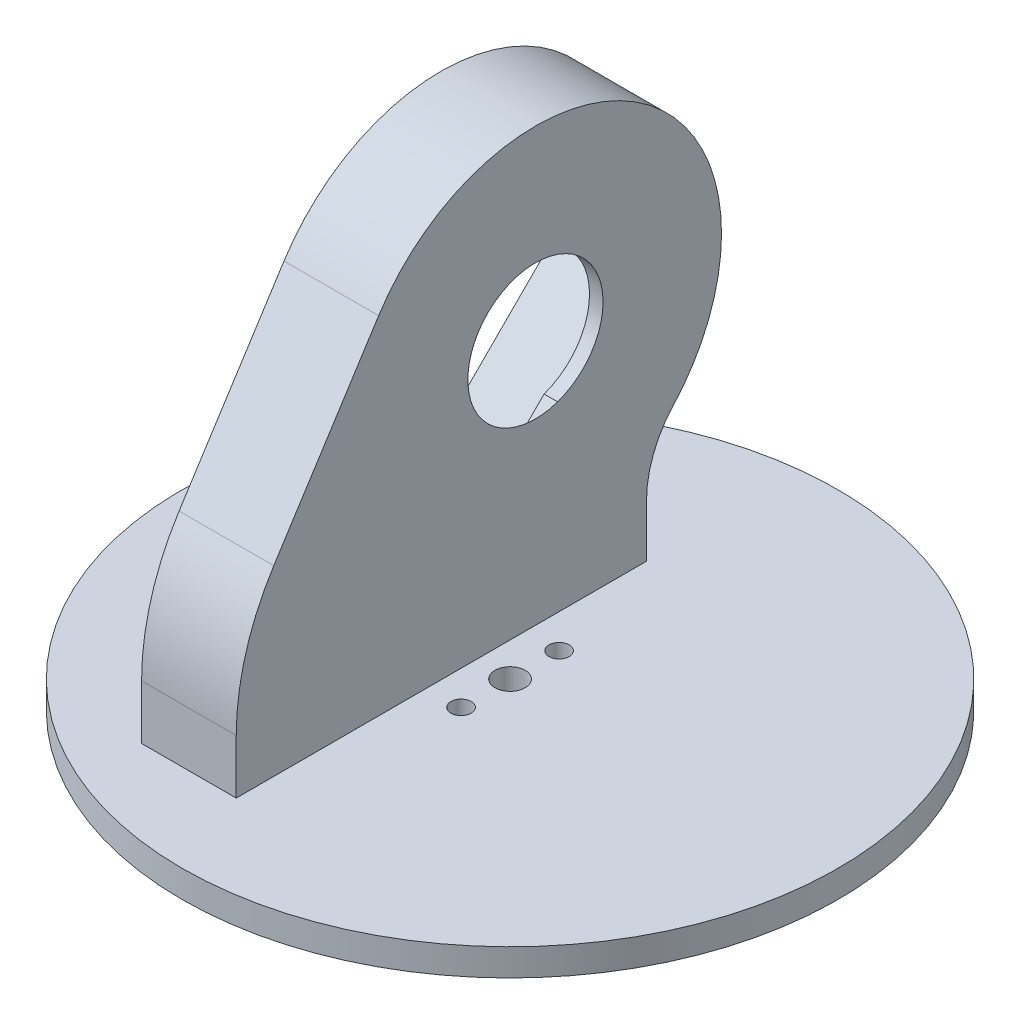
SolidWorks part; units mm, degrees
material "Acrylic (Medium-high impact)"
ref_plane "Front Plane" through (0, 0, 0) normal (0, 0, 1) x (1, 0, 0)
ref_plane "Top Plane" through (0, 0, 0) normal (0, 1, 0) x (1, 0, 0)
ref_plane "Right Plane" through (0, 0, 0) normal (1, 0, 0) x (0, 0, -1)
sketch "Sketch1" plane through (0, 0, 0) normal (0, 1, 0) x (1, 0, 0)
  line L0 (0, 51.8022) -> (0, -53.3582) construction
  circle A0 centre (0, 0) radius 48.5
  circle A1 centre (0, 7.25) radius 1.5
  circle A2 centre (0, -7.25) radius 1.5
  circle A3 centre (0, 0) radius 2.2356
  point P12 (0, 0)
  dimension "D1" = 97
  dimension "D2" = 3
  dimension "D3" = 3
  dimension "D4" = 14.5
  dimension "D5" = 7.25
extrude "Boss-Extrude2" add sketch "Sketch1" along normal blind 4
ref_plane "Plane2" through (-5, 0, 0) normal (1, 0, 0) x (0, 0, -1)
sketch "Sketch6" plane through (-5, 0, 0) normal (1, 0, 0) x (0, 0, -1)
  line L0 (25.18, 4) -> (-35.5, 4)
  line L1 (25.18, 4) -> (25.18, 11.7973)
  line L2 (-35.5, 4) -> (-35.5, 12.0173)
  line L3 (-29.9527, 30.9934) -> (-14.4381, 55.2614)
  line L4 (48.5, 4) -> (-48.5, 4) construction
  arc A0 (25.18, 11.7973) -> (29.0927, 21.9003) centre (40.18, 11.7973) cw
  arc A1 (29.0927, 21.9003) -> (-14.4381, 55.2614) centre (8.75, 40.4373) ccw
  arc A2 (-35.5, 12.0173) -> (-29.9527, 30.9934) centre (-0.27, 12.0173) cw
  circle A3 centre (8.75, 40.4373) radius 10
  point P3 (-5.16, 4)
  dimension "D2" = 20
  dimension "D1" = 13
extrude "Boss-Extrude3" add sketch "Sketch6" along normal blind 0.0001 and the other way blind 14
sketch "Sketch7" plane through (-19, 0, 0) normal (-1, 0, 0) x (0, 0, 1)
  line L0 (-8.75, 40.4373) -> (-15.8211, 47.5083) construction
  line L1 (-15.8211, 47.5083) -> (14.2381, 17.4492) construction
  line L2 (14.2381, 17.4492) -> (-20.8548, 52.5421) construction
  circle A0 centre (-8.75, 40.4373) radius 10 construction
sketch "Sketch9" plane through (-19, 0, 0) normal (-1, 0, 0) x (0, 0, 1)
  line L0 (5.5689, 11.2691) -> (20.4182, 26.1183)
  line L1 (5.5689, 11.2691) -> (-23.4225, 40.2605)
  line L2 (20.4182, 26.1183) -> (-8.5732, 55.1097)
  line L3 (-23.4225, 40.2605) -> (-8.5732, 55.1097)
  line L5 (14.2381, 17.4492) -> (-20.8548, 52.5421) construction
  line L6 (-15.8211, 47.5083) -> (14.2381, 17.4492) construction
  line L7 (-8.75, 40.4373) -> (-15.8211, 47.5083) construction
  line L8 (-8.75, 40.4373) -> (-20.8548, 28.3324) construction
  dimension "D1" = 10.25
  dimension "D2" = 10.5
  dimension "D3" = 41
  dimension "D4" = 10.5
extrude "Cut-Extrude1" cut sketch "Sketch9" against normal blind 12
sketch "Sketch11" plane through (-19, 0, 0) normal (-1, 0, 0) x (0, 0, 1)
  line L1 (14.2381, 17.4492) -> (-20.8548, 52.5421) construction
  line L2 (-8.75, 40.4373) -> (-30.3394, 62.0267) construction
  line L3 (5.9225, 40.614) -> (-16.7991, 17.8925) construction
  line L4 (20.4182, 26.1183) -> (-8.5732, 55.1097) construction
  line L8 (-15.8211, 47.5083) -> (14.2381, 17.4492) construction
  circle A0 centre (-15.1493, 53.9076) radius 1.3
  circle A1 centre (-22.2204, 46.8366) radius 1.3
  circle A2 centre (12.145, 12.4712) radius 1.3
  circle A3 centre (19.2161, 19.5423) radius 1.3
  dimension "D3" = 2.6
  dimension "D1" = 48.6
  dimension "D2" = 5
  dimension "D4" = 5
extrude "Cut-Extrude3" cut sketch "Sketch11" against normal blind 4
sketch "Sketch16" plane through (-19, 0, 0) normal (-1, 0, 0) x (0, 0, 1)
  line L0 (48.5, 4) -> (-48.5, 4) construction
  line L1 (35.5, 4) -> (-25.18, 4) construction
  line L2 (-16.8751, 4) -> (28.7375, 4)
  spline S0 degree 3 poles (-16.8751, 4) (-17.737, 15.1601) (-34.125, 25.1593) (-33.933, 51.0007) (-17.2151, 67.5551) (7.9829, 62.5246) (20.7157, 35.8056) (37.0291, 21.2545) (28.7375, 4) knots 0 0 0 0 0.199147 0.316662 0.448197 0.600919 0.72518 1 1 1 1
extrude "Cut-Extrude4" cut sketch "Sketch16" against normal blind 2
sketch "Sketch18" plane through (-7, 0, 0) normal (-1, 0, 0) x (0, 0, 1)
  line L0 (-8.75, 40.4373) -> (8.857, 22.8303)
  line L1 (-15.114, 34.0733) -> (-2.386, 46.8012)
  line L2 (2.493, 16.4663) -> (15.2209, 29.1943)
  line L3 (-2.386, 46.8012) -> (15.2209, 29.1943)
  line L4 (-15.8211, 47.5083) -> (14.2381, 17.4492) construction
  line L6 (13.3782, 18.3091) -> (-15.8211, 47.5083) construction
  line L7 (-15.114, 34.0733) -> (2.493, 16.4663)
  line L8 (11.7278, 25.7012) -> (5.9861, 19.9594)
  circle A0 centre (-8.75, 40.4373) radius 10 construction
  arc A1 (5.9861, 19.9594) -> (11.7278, 25.7012) centre (8.857, 22.8303) ccw
  circle M11 centre (-8.75, 40.4373) radius 10
  dimension "D3" = 4.06
  dimension "D1" = 24.9
  dimension "D2" = 9
extrude "Cut-Extrude5" cut sketch "Sketch18" against normal blind 2 contours L6 A1 L2 | A1 L6 L2 | L3 L0 L2 M11 | L7 L2 L0 M11
